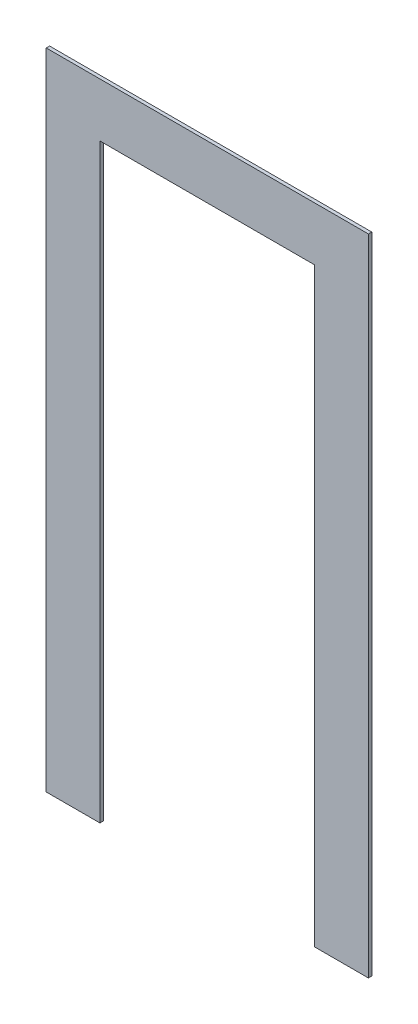
SolidWorks part; units mm, degrees
ref_plane "Front Plane" through (0, 0, 0) normal (0, 0, 1) x (1, 0, 0)
ref_plane "Top Plane" through (0, 0, 0) normal (0, 1, 0) x (1, 0, 0)
ref_plane "Right Plane" through (0, 0, 0) normal (1, 0, 0) x (0, 0, -1)
sketch "Sketch2" plane through (0, 0, 0) normal (0, 0, 1) x (1, 0, 0)
  line L1 (0, 0) -> (304.8, 0)
  line L2 (0, 0) -> (0, 609.6)
  line L3 (0, 609.6) -> (304.8, 609.6)
  line L4 (304.8, 0) -> (304.8, 609.6)
  dimension "D1" = 304.8
  dimension "D2" = 609.6
extrude "Boss-Extrude1" add sketch "Sketch2" along normal blind 3.175
sketch "Sketch3" plane through (0, 0, 3.175) normal (0, 0, 1) x (1, 0, 0)
  line L0 (0, 0) -> (304.8, 0) construction
  line L1 (50.8, 0) -> (254, 0)
  line L2 (50.8, 0) -> (50.8, 558.8)
  line L3 (50.8, 558.8) -> (254, 558.8)
  line L4 (254, 0) -> (254, 558.8)
  line L5 (0, 609.6) -> (0, 0) construction
  line L6 (304.8, 0) -> (304.8, 609.6) construction
  line L7 (304.8, 609.6) -> (0, 609.6) construction
  dimension "D1" = 50.8
  dimension "D2" = 50.8
  dimension "D3" = 50.8
extrude "Cut-Extrude1" cut sketch "Sketch3" against normal up to surface (3.175 mm away) up to face at (152.4, 304.8, 0)
